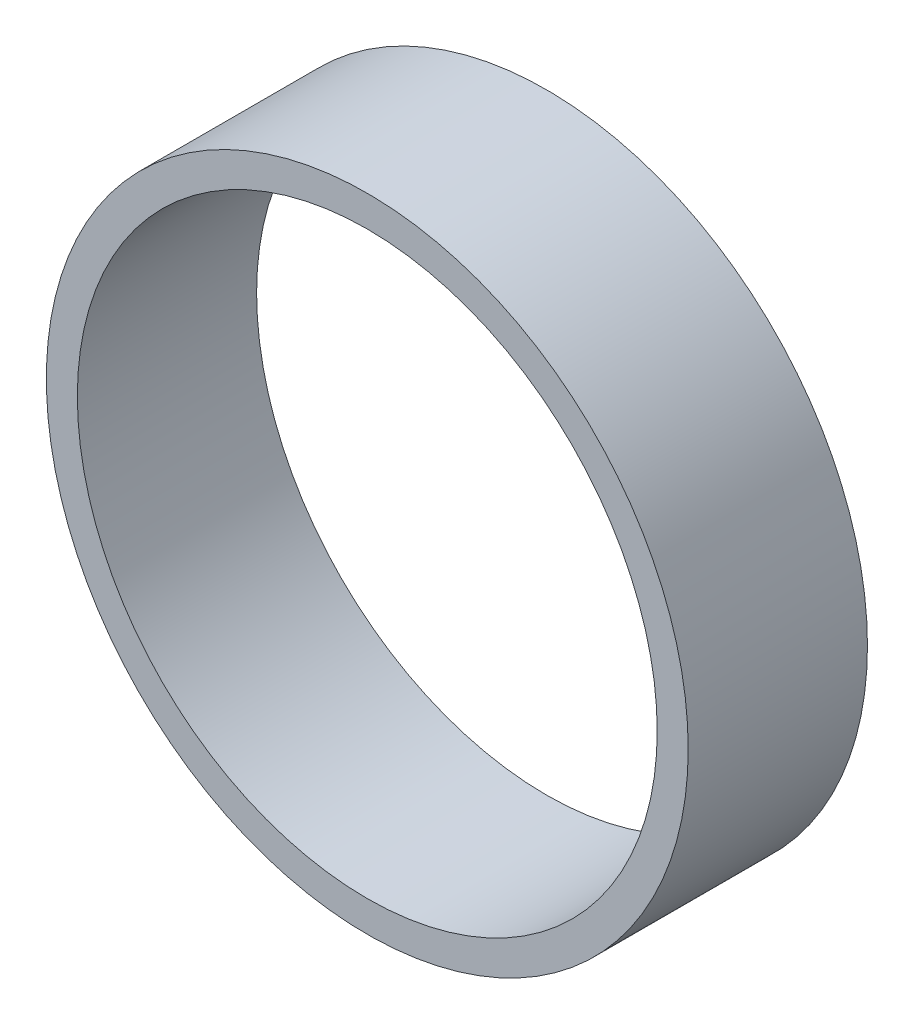
SolidWorks part; units mm, degrees
ref_plane "Front Plane" through (0, 0, 0) normal (1, 0, 0) x (0, 1, 0)
ref_plane "Top Plane" through (0, 0, 0) normal (0, 0, 1) x (0, 1, 0)
ref_plane "Right Plane" through (0, 0, 0) normal (0, 1, 0) x (-1, 0, 0)
sketch "Sketch1" plane through (0, 0, 0) normal (0, 0, 1) x (0, 1, 0)
  circle A0 centre (0, 0) radius 37.0407
  circle A1 centre (0, 0) radius 41
  dimension "D1" = 82
extrude "Boss-Extrude1" add sketch "Sketch1" along normal blind 22.9
